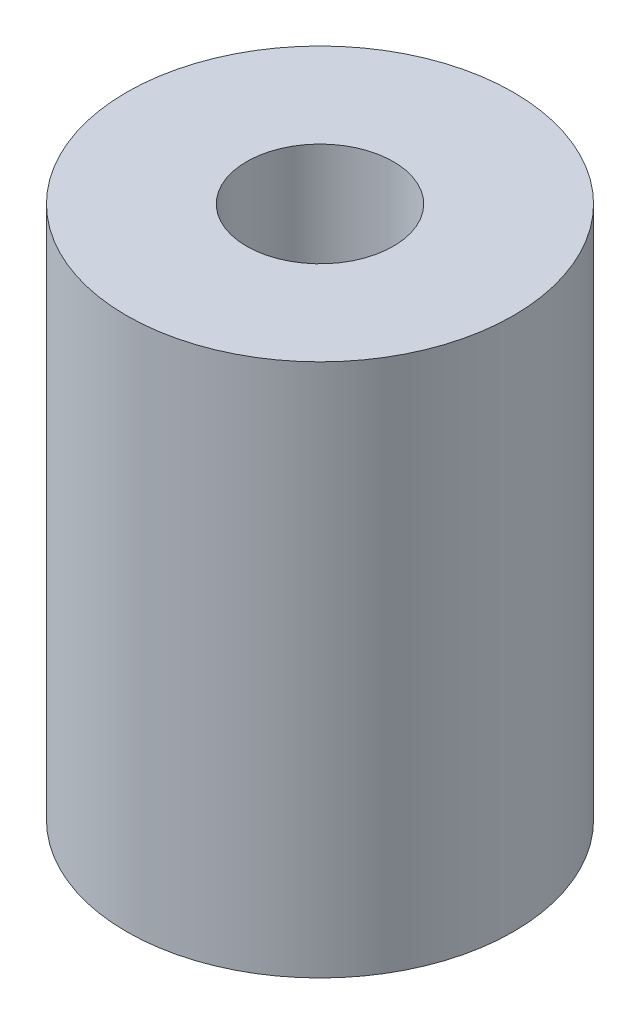
SolidWorks part; units mm, degrees
ref_plane "Front Plane" through (0, 0, 0) normal (0, 0, 1) x (1, 0, 0)
ref_plane "Top Plane" through (0, 0, 0) normal (0, 1, 0) x (1, 0, 0)
ref_plane "Right Plane" through (0, 0, 0) normal (1, 0, 0) x (0, 0, -1)
sketch "Sketch1" plane through (0, 0, 0) normal (0, 1, 0) x (1, 0, 0)
  circle A0 centre (0, 0) radius 2.9
  circle A1 centre (0, 0) radius 1.1
  dimension "D1" = 5.8
  dimension "D2" = 2.2
extrude "Boss-Extrude1" add sketch "Sketch1" along normal blind 8
